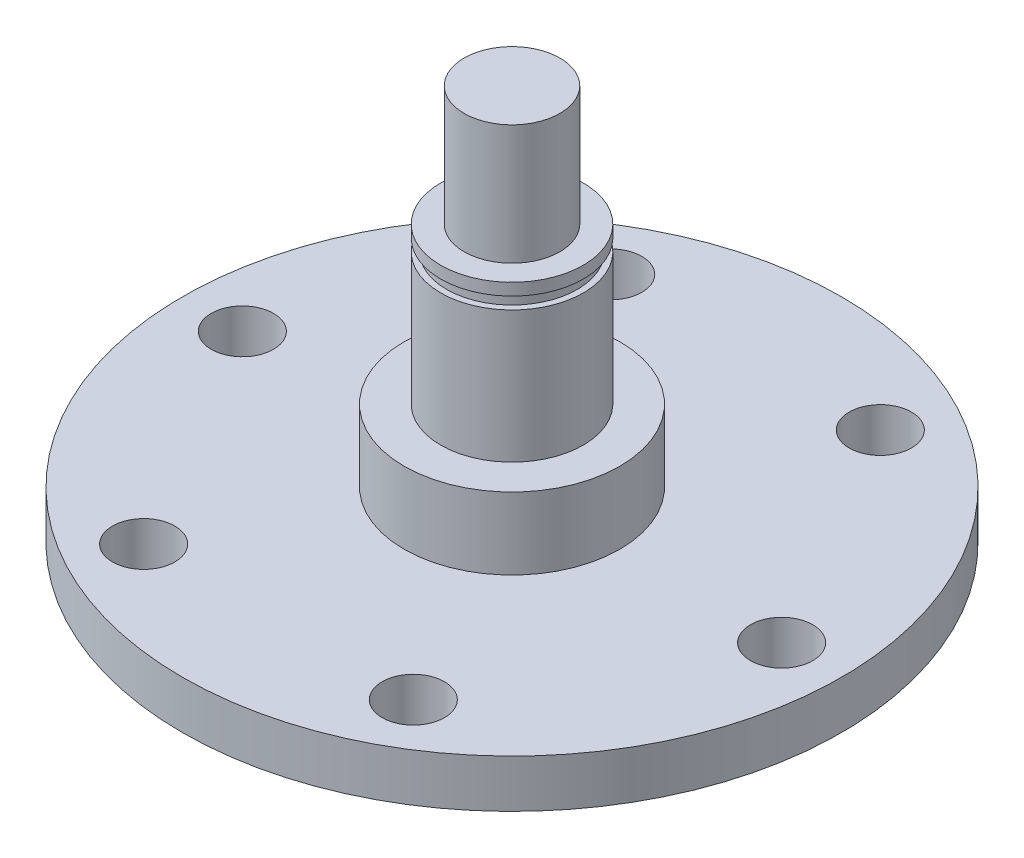
SolidWorks part; units mm, degrees
material "6063-T6"
ref_plane "前视基准面" through (0, 0, 0) normal (0, 0, 1) x (1, 0, 0)
ref_plane "上视基准面" through (0, 0, 0) normal (0, 1, 0) x (1, 0, 0)
ref_plane "右视基准面" through (0, 0, 0) normal (1, 0, 0) x (0, 0, -1)
sketch "草图1" plane through (0, 0, 0) normal (0, 0, 1) x (1, 0, 0)
  line L0 (0, 0) -> (27.5, 0)
  line L1 (27.5, 0) -> (27.5, 4)
  line L2 (27.5, 4) -> (9, 4)
  line L3 (9, 4) -> (9, 10)
  line L4 (9, 10) -> (5.95, 10)
  line L5 (5.95, 10) -> (5.95, 21)
  line L6 (5.95, 21) -> (5.45, 21)
  line L7 (5.45, 21) -> (5.45, 22)
  line L8 (5.45, 22) -> (5.95, 22)
  line L9 (5.95, 22) -> (5.95, 23)
  line L10 (5.95, 23) -> (4, 23)
  line L11 (0, 23.5) -> (0, 0)
  line L12 (4, 23) -> (4, 33)
  line L13 (4, 33) -> (0, 33)
  line L14 (0, 33) -> (0, 23.5)
  dimension "D1" = 11
  dimension "D2" = 4
  dimension "D3" = 6
  dimension "D4" = 27.5
  dimension "D5" = 1
  dimension "D6" = 1
  dimension "D7" = 0.5
  dimension "D8" = 10
  dimension "D9" = 9
  dimension "D11" = 5.95
  dimension "D12" = 4
revolve "旋转1" add sketch "草图1" angle 360 about L11
sketch "草图2" plane through (0, 4, 0) normal (0, 1, 0) x (1, 0, 0)
  circle A0 centre (22.5, 0) radius 2.6
  circle A1 centre (11.25, -19.4856) radius 2.6
  circle A2 centre (-11.25, -19.4856) radius 2.6
  circle A3 centre (-22.5, 0) radius 2.6
  circle A4 centre (-11.25, 19.4856) radius 2.6
  circle A5 centre (11.25, 19.4856) radius 2.6
  point P15 (0, 0)
  dimension "D1" = 6
extrude "切除-拉伸1" cut sketch "草图2" against normal through all
sketch "草图3" plane through (0, 0, 0) normal (1, 0, 0) x (0, 0, -1)
  line L1 (-28.9663, 5.4394) -> (29.3531, 5.4394)
  line L2 (-28.9663, 5.4394) -> (-28.9663, -1.9859)
  line L3 (-28.9663, -1.9859) -> (29.3531, -1.9859)
  line L4 (29.3531, 5.4394) -> (29.3531, -1.9859)
  line L5 (0.1934, -1.9859) -> (0.1934, 5.4394) construction
  line L6 (-28.9663, 1.7268) -> (29.3531, 1.7268) construction
  point P212 (0.1934, 1.7268)
